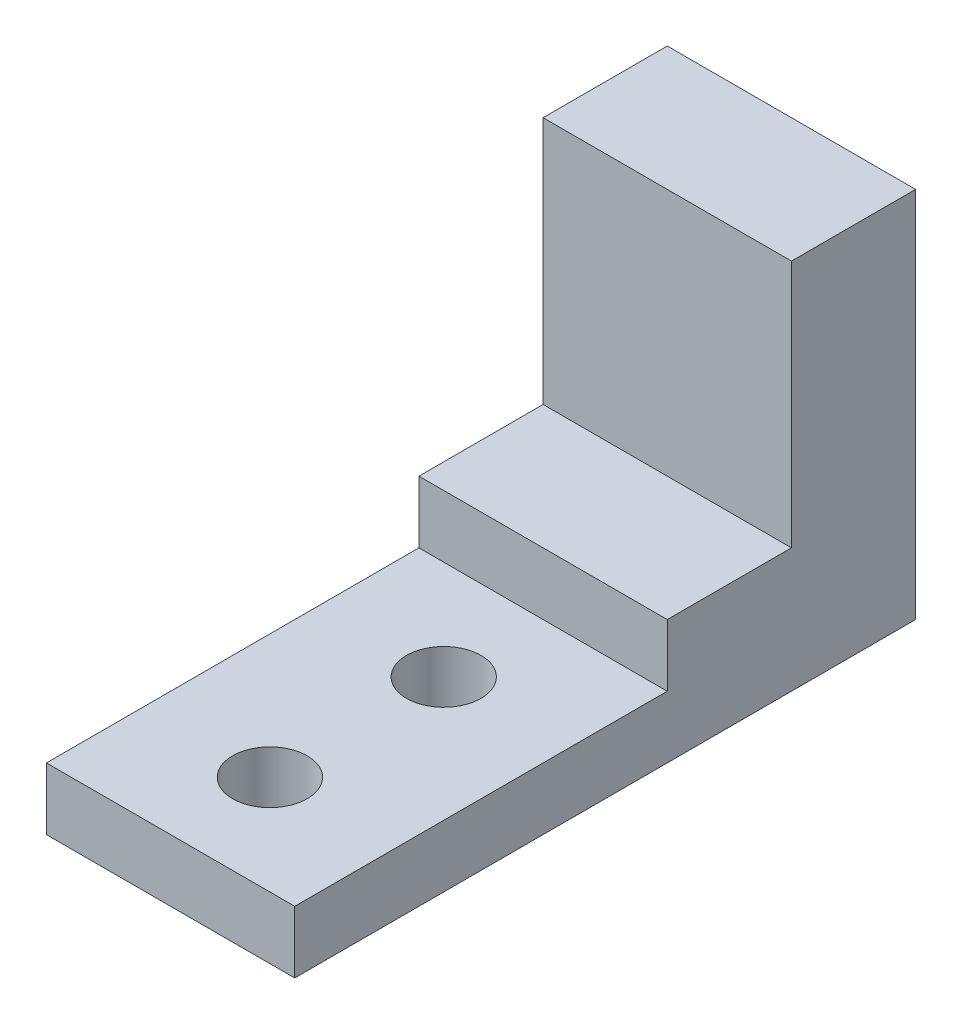
SolidWorks part; units mm, degrees
ref_plane "Front Plane" through (0, 0, 0) normal (0, 0, 1) x (1, 0, 0)
ref_plane "Top Plane" through (0, 0, 0) normal (0, 1, 0) x (1, 0, 0)
ref_plane "Right Plane" through (0, 0, 0) normal (1, 0, 0) x (0, 0, -1)
sketch "Sketch1" plane through (0, 0, 0) normal (0, 0, 1) x (1, 0, 0)
  line L1 (0, 0) -> (10, 0)
  line L2 (0, 0) -> (0, -2.5)
  line L3 (0, -2.5) -> (10, -2.5)
  line L4 (10, 0) -> (10, -2.5)
  dimension "D1" = 10
  dimension "D2" = 2.5
extrude "Boss-Extrude1" add sketch "Sketch1" along normal blind 15
sketch "Sketch2" plane through (0, 0, 0) normal (0, 1, 0) x (1, 0, 0)
  line L0 (10, -15) -> (0, -15) construction
  line L1 (10, 0) -> (0, 0) construction
  circle A0 centre (5, -11) radius 1.5
  circle A1 centre (5, -4) radius 1.5
  dimension "D1" = 4
  dimension "D2" = 4
extrude "Cut-Extrude1" cut sketch "Sketch2" against normal blind 15
sketch "Sketch3" plane through (0, 0, 0) normal (0, 0, -1) x (-1, 0, 0)
  line L1 (-10, -2.5) -> (0, -2.5)
  line L2 (-10, -2.5) -> (-10, 2.5)
  line L3 (-10, 2.5) -> (0, 2.5)
  line L4 (0, -2.5) -> (0, 2.5)
  dimension "D1" = 5
extrude "Boss-Extrude2" add sketch "Sketch3" along normal blind 10
sketch "Sketch4" plane through (0, 2.5, 0) normal (0, 1, 0) x (1, 0, 0)
  line L0 (10, 10) -> (10, 0) construction
  line L1 (0, 10) -> (10, 10)
  line L2 (0, 10) -> (0, 5)
  line L3 (0, 5) -> (10, 5)
  line L4 (10, 10) -> (10, 5)
extrude "Boss-Extrude3" add sketch "Sketch4" along normal blind 10
